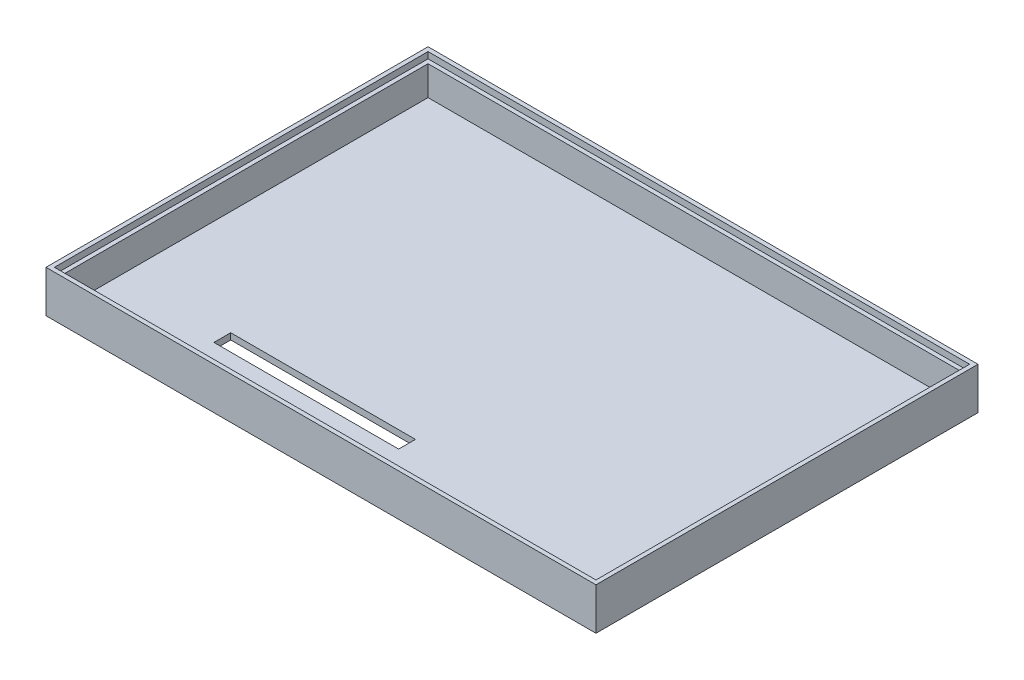
SolidWorks part; units mm, degrees
ref_plane "Front Plane" through (0, 0, 0) normal (0, 0, 1) x (1, 0, 0)
ref_plane "Top Plane" through (0, 0, 0) normal (0, 1, 0) x (1, 0, 0)
ref_plane "Right Plane" through (0, 0, 0) normal (1, 0, 0) x (0, 0, -1)
sketch "Sketch1" plane through (0, 0, 0) normal (0, 1, 0) x (1, 0, 0)
  line L1 (-63.5, -43.5) -> (63.5, -43.5)
  line L2 (-63.5, -43.5) -> (-63.5, 43.5)
  line L3 (-63.5, 43.5) -> (63.5, 43.5)
  line L4 (63.5, -43.5) -> (63.5, 43.5)
  line L5 (-63.5, -43.5) -> (63.5, 43.5) construction
  line L6 (-63.5, 43.5) -> (63.5, -43.5) construction
  point P0 (0, 0)
  dimension "D1" = 127
  dimension "D2" = 87
extrude "Boss-Extrude1" add sketch "Sketch1" along normal blind 1.5
sketch "Sketch2" plane through (0, 0, 0) normal (0, 1, 0) x (1, 0, 0)
  line L21 (-65.5, 45.5) -> (-65.5, -45.5)
  line L22 (-65.5, -45.5) -> (65.5, -45.5)
  line L23 (65.5, -45.5) -> (65.5, 45.5)
  line L24 (65.5, 45.5) -> (-65.5, 45.5)
  line L25 (-65.5, 45.5) -> (-65.5, -45.5)
  line L26 (-65.5, -45.5) -> (65.5, -45.5)
  line L27 (65.5, -45.5) -> (65.5, 45.5)
  line L28 (65.5, 45.5) -> (-65.5, 45.5)
  line L39 (-63.5, -43.5) -> (63.5, -43.5)
  line L40 (63.5, -43.5) -> (63.5, 43.5)
  line L41 (63.5, 43.5) -> (-63.5, 43.5)
  line L42 (-63.5, 43.5) -> (-63.5, -43.5)
  line L43 (-63.5, -43.5) -> (63.5, -43.5)
  line L44 (63.5, -43.5) -> (63.5, 43.5)
  line L45 (63.5, 43.5) -> (-63.5, 43.5)
  line L46 (-63.5, 43.5) -> (-63.5, -43.5)
  dimension "D1" = 2
  dimension "D2" = 0
extrude "Boss-Extrude2" add sketch "Sketch2" along normal blind 10
sketch "Sketch3" plane through (0, 0, 0) normal (0, -1, 0) x (1, 0, 0)
  line L0 (-65.5, -45.5) -> (-65.5, 45.5) construction
  line L1 (-38.5, 32.5) -> (5.5, 32.5)
  line L2 (-38.5, 32.5) -> (-38.5, 28.5)
  line L3 (-38.5, 28.5) -> (5.5, 28.5)
  line L4 (5.5, 32.5) -> (5.5, 28.5)
  line L5 (-38.5, 32.5) -> (5.5, 28.5) construction
  line L6 (-38.5, 28.5) -> (5.5, 32.5) construction
  line L7 (-65.5, 45.5) -> (65.5, 45.5) construction
  point P0 (-16.5, 30.5)
  dimension "D1" = 4
  dimension "D2" = 44
  dimension "D3" = 27
  dimension "D4" = 13
extrude "Cut-Extrude1" cut sketch "Sketch3" against normal up to next
sketch "Sketch5" plane through (0, 10, 0) normal (0, 1, 0) x (1, 0, 0)
  line L8 (64.5, 44.5) -> (-64.5, 44.5)
  line L9 (-64.5, 44.5) -> (-64.5, -44.5)
  line L10 (-64.5, -44.5) -> (64.5, -44.5)
  line L11 (64.5, -44.5) -> (64.5, 44.5)
  line L12 (64.5, 44.5) -> (-64.5, 44.5)
  line L13 (-64.5, 44.5) -> (-64.5, -44.5)
  line L14 (-64.5, -44.5) -> (64.5, -44.5)
  line L15 (64.5, -44.5) -> (64.5, 44.5)
  line L26 (-63.5, -43.5) -> (63.5, -43.5)
  line L27 (63.5, -43.5) -> (63.5, 43.5)
  line L28 (63.5, 43.5) -> (-63.5, 43.5)
  line L29 (-63.5, 43.5) -> (-63.5, -43.5)
  line L30 (-63.5, -43.5) -> (63.5, -43.5)
  line L31 (63.5, -43.5) -> (63.5, 43.5)
  line L32 (63.5, 43.5) -> (-63.5, 43.5)
  line L33 (-63.5, 43.5) -> (-63.5, -43.5)
  dimension "D1" = 1
  dimension "D2" = 0
extrude "Cut-Extrude3" cut sketch "Sketch5" against normal blind 1.5
